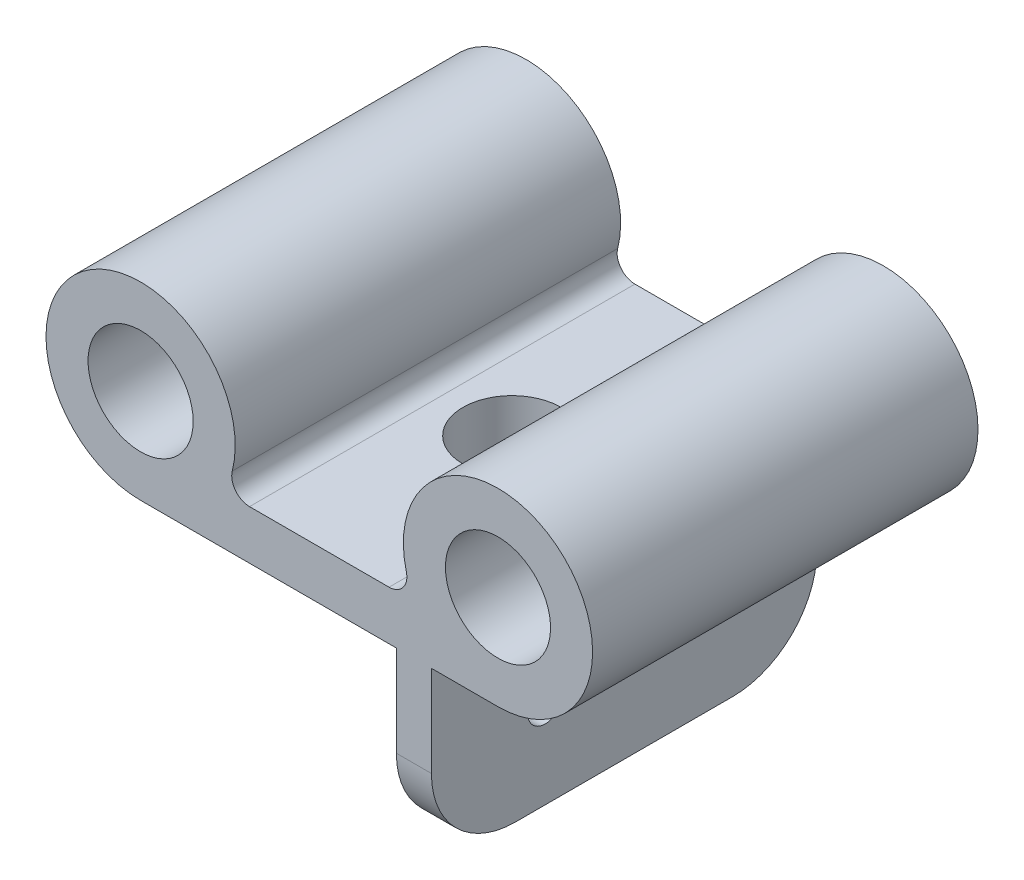
SolidWorks part; units mm, degrees
material "ABS"
ref_plane "Front Plane" through (0, 0, 0) normal (0, 0, 1) x (1, 0, 0)
ref_plane "Top Plane" through (0, 0, 0) normal (0, 1, 0) x (1, 0, 0)
ref_plane "Right Plane" through (0, 0, 0) normal (1, 0, 0) x (0, 0, -1)
sketch "Sketch1" plane through (0, 0, 0) normal (0, 0, 1) x (1, 0, 0)
  line L0 (0, 17.1332) -> (0, -18.0069) construction
  line L2 (-13.6678, -6.5) -> (13.6678, -6.5)
  line L4 (-25.5, -13.5) -> (25.5, -13.5)
  circle A0 centre (-25.5, 0) radius 7.5
  arc A1 (-13.6678, -6.5) -> (-25.5, -13.5) centre (-25.5, 0) ccw
  arc A2 (13.6678, -6.5) -> (25.5, -13.5) centre (25.5, 0) cw
  circle A3 centre (25.5, 0) radius 7.5
  circle A4 centre (-25.5, 0) radius 13.5 construction
  dimension "D1" = 15
  dimension "D2" = 6
  dimension "D3" = 25.5
  dimension "D4" = 7
extrude "Boss-Extrude1" add sketch "Sketch1" along normal blind 55
fillet "Fillet1" radius 2.54 2 edges at (13.6678, -6.5, 27.5) (-13.6678, -6.5, 27.5)
sketch "Sketch2" plane through (0, -13.5, 0) normal (0, -1, 0) x (1, 0, 0)
  line L1 (25.5, 0) -> (-25.5, 55) construction
  line L2 (-25.5, 0) -> (25.5, 0) construction
  line L3 (16, 0) -> (11, 0)
  line L4 (16, 0) -> (16, 55)
  line L5 (16, 55) -> (11, 55)
  line L6 (11, 0) -> (11, 55)
  line L7 (-25.5, 55) -> (25.5, 55) construction
  circle A0 centre (0, 27.5) radius 7
  line M5 (-25.5, 0) -> (25.5, 0)
  line M7 (25.5, 55) -> (-25.5, 55)
  dimension "D2" = 5
  dimension "D1" = 14
  dimension "D3" = 11
extrude "Boss-Extrude2" add sketch "Sketch2" along normal blind 25 contours L1 L4 L6 M7 | L4 L1 L6 M5
sketch "Sketch4" plane through (0, -13.5, 0) normal (0, -1, 0) x (1, 0, 0)
  line L0 (-25.5, 27.5) -> (11, 27.5) construction
  line L1 (-25.5, 55) -> (-25.5, 0) construction
  line L2 (11, 0) -> (11, 55) construction
  circle A0 centre (0, 27.5) radius 7
  dimension "D1" = 14
  dimension "D2" = 11
extrude "Cut-Extrude1" cut sketch "Sketch4" against normal through all
fillet "Fillet2" radius 12 2 edges at (13.5, -38.5, 55) (13.5, -38.5, 0)
extrude "Cut-Extrude2" cut sketch "Sketch5" against normal through all
sketch "Sketch5" plane through (11, 11.1941, 4.4683) normal (-1, 0, 0) x (0, 0, 1)
  circle A0 centre (11.7817, -37.1941) radius 2.5
  circle A1 centre (34.2817, -37.1941) radius 2.5
